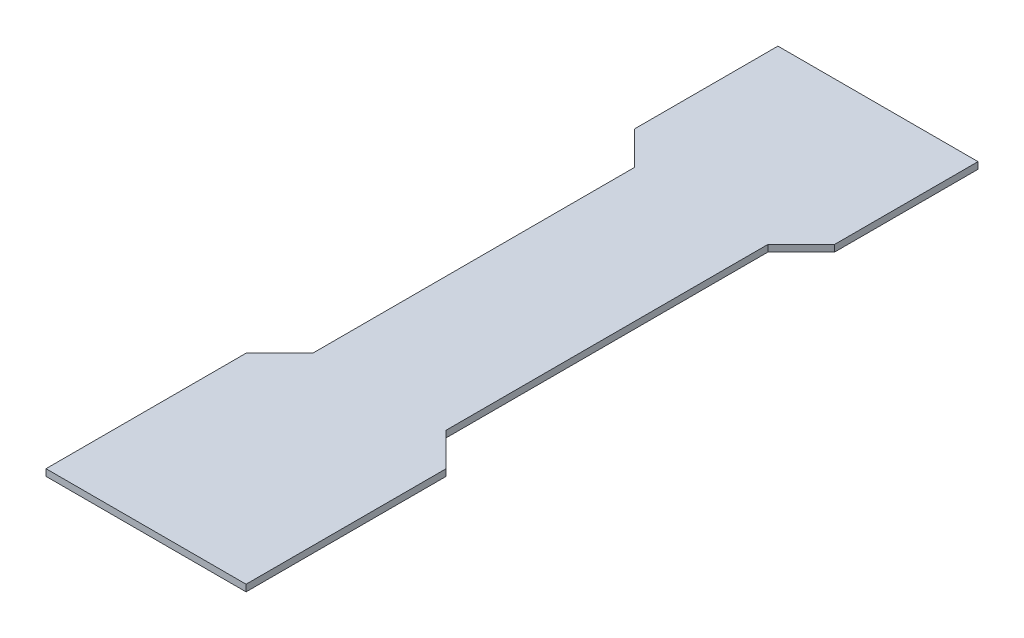
SolidWorks part; units mm, degrees
ref_plane "前视基准面" through (0, 0, 0) normal (0, 0, 1) x (1, 0, 0)
ref_plane "上视基准面" through (0, 0, 0) normal (0, 1, 0) x (1, 0, 0)
ref_plane "右视基准面" through (0, 0, 0) normal (1, 0, 0) x (0, 0, -1)
sketch "草图1" plane through (0, 0, 0) normal (0, 1, 0) x (1, 0, 0)
  line L0 (-30, -260) -> (-30, -320)
  line L6 (-30, -143.5) -> (-20, -153.5)
  line L8 (-20, -240) -> (-20, -153.5)
  line L21 (-30, -143.5) -> (-30, -100.5)
  line L22 (-30, -260) -> (-20, -250)
  line L23 (-20, -250) -> (-20, -240)
  line L24 (-30, -320) -> (30, -320)
  line L25 (-30, -100.5) -> (30, -100.5)
  line L27 (20, -250) -> (20, -240)
  line L28 (30, -260) -> (20, -250)
  line L29 (30, -143.5) -> (30, -100.5)
  line L30 (20, -240) -> (20, -153.5)
  line L31 (30, -143.5) -> (20, -153.5)
  line L32 (30, -260) -> (30, -320)
  point P12 (0, -320)
extrude "凸台-拉伸1" add sketch "草图1" along normal blind 2
